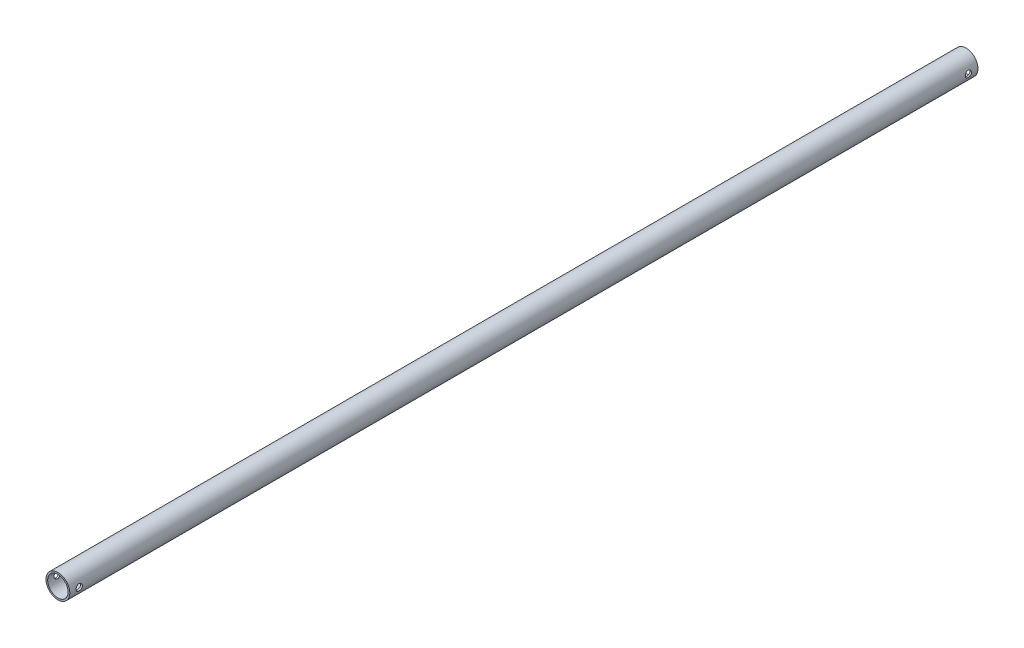
SolidWorks part; units mm, degrees
material "Hexcel AS4C (3000 Filaments)"
ref_plane "Front Plane" through (0, 0, 0) normal (0, 0, 1) x (1, 0, 0)
ref_plane "Top Plane" through (0, 0, 0) normal (0, 1, 0) x (1, 0, 0)
ref_plane "Right Plane" through (0, 0, 0) normal (1, 0, 0) x (0, 0, -1)
sketch "Sketch1" plane through (0, 0, 0) normal (0, 0, 1) x (1, 0, 0)
  circle A0 centre (0, 0) radius 5.9944
  circle A1 centre (0, 0) radius 4.953
  dimension "D1" = 11.9888
  dimension "D2" = 9.906
extrude "Boss-Extrude1" add sketch "Sketch1" along normal blind 457.2
sketch "Sketch8" plane through (0, 0, 0) normal (0, 0, -1) x (-1, 0, 0)
  circle A0 centre (0, 0) radius 5.1435
  dimension "D1" = 10.287
extrude "Cut-Extrude2" cut sketch "Sketch8" against normal blind 25.4
sketch "Sketch9" plane through (0, 0, 457.2) normal (0, 0, 1) x (1, 0, 0)
  circle A0 centre (0, 0) radius 5.1435
  dimension "D1" = 10.287
extrude "Cut-Extrude3" cut sketch "Sketch9" against normal blind 25.4
ref_plane "Plane1" through (-5.9944, 0, 0) normal (-1, 0, 0) x (0, 0, 1)
hole_wizard "1/8 (0.125) Diameter Hole1" positions "Sketch11" profile "Sketch12" hole size "1/8" standard "ANSI Inch" end condition through all
sketch "Sketch11" plane through (-5.9944, 0, 0) normal (-1, 0, 0) x (0, 0, 1)
  line L0 (0, 0) -> (457.2, 0) construction
  line L2 (457.2, -5.9944) -> (457.2, 5.9944) construction
  point P0 (452.4375, 0)
  point P2 (4.7625, 0)
  point P10 (0, 0)
  point P13 (452.4375, 0)
  point P14 (9.6936, 0)
  dimension "D1" = 4.7625
  dimension "D2" = 4.7625
sketch "Sketch12" plane through (-5.9944, 0, 452.4375) normal (0, 1, 0) x (0, 0, 1)
  line L0 (0, 0) -> (0, 11.9888)
  line L1 (0, 11.9888) -> (1.5875, 11.9888)
  line L2 (1.5875, 11.9888) -> (1.5875, 0)
  line L5 (1.5875, 0) -> (0, 0)
  line L11 (0, -6.35) -> (0, 107.95) construction
  dimension "Thru Hole Dia." = 3.175
  dimension "Thru Hole Depth" = 11.9888
